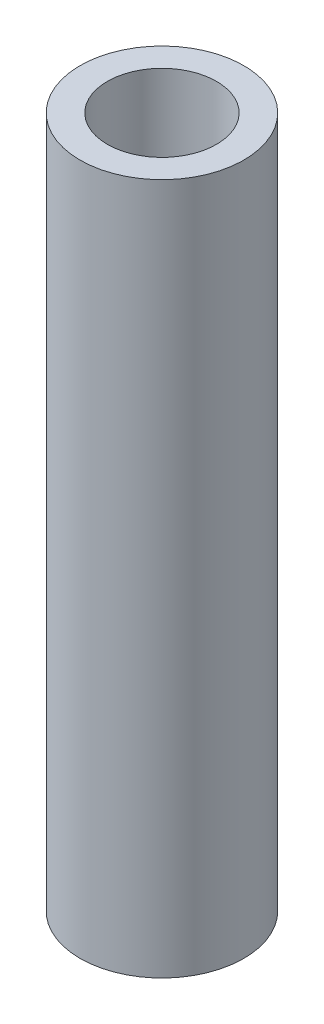
SolidWorks part; units mm, degrees
ref_plane "Front Plane" through (0, 0, 0) normal (0, 0, 1) x (1, 0, 0)
ref_plane "Top Plane" through (0, 0, 0) normal (0, 1, 0) x (1, 0, 0)
ref_plane "Right Plane" through (0, 0, 0) normal (1, 0, 0) x (0, 0, -1)
sketch "Sketch1" plane through (0, 0, 0) normal (0, 1, 0) x (1, 0, 0)
  circle A0 centre (0, 0) radius 2.25
  circle A1 centre (0, 0) radius 1.5
  dimension "D1" = 4.5
  dimension "D2" = 3
extrude "Boss-Extrude1" add sketch "Sketch1" along normal blind 19
